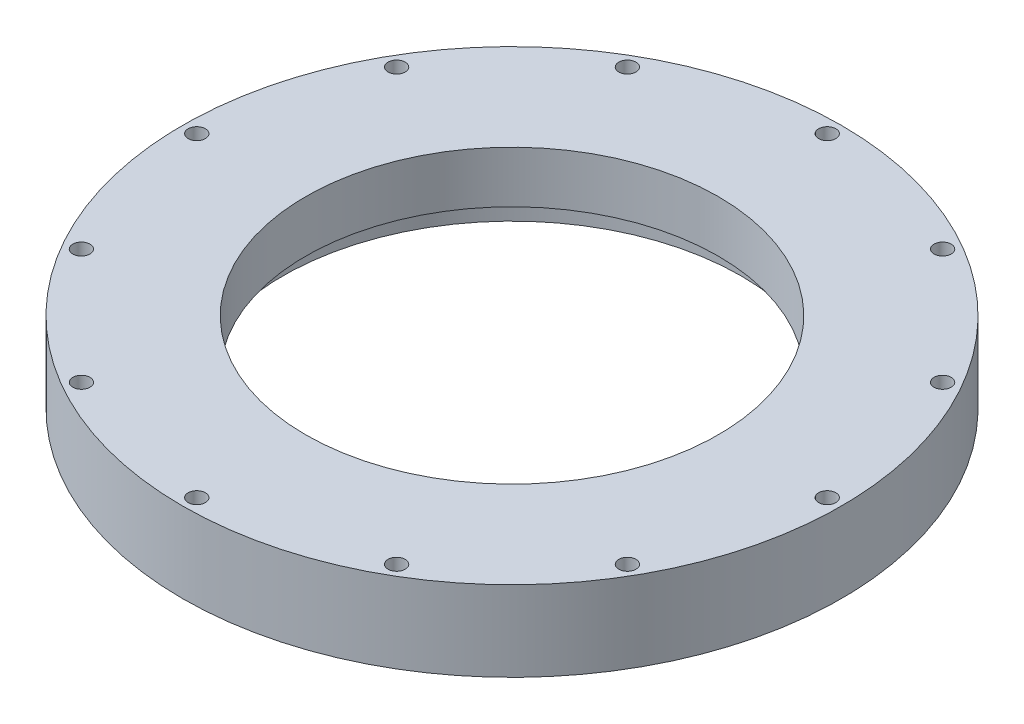
SolidWorks part; units mm, degrees
ref_plane "Front Plane" through (0, 0, 0) normal (0, 0, 1) x (1, 0, 0)
ref_plane "Top Plane" through (0, 0, 0) normal (0, 1, 0) x (1, 0, 0)
ref_plane "Right Plane" through (0, 0, 0) normal (1, 0, 0) x (0, 0, -1)
sketch "Sketch1" plane through (0, 0, 0) normal (0, 1, 0) x (1, 0, 0)
  circle A12 centre (0, 0) radius 40
  circle A13 centre (0, 0) radius 57.5
  circle A14 centre (0, 0) radius 55 construction
  circle A15 centre (0, 55) radius 1.5
  circle A16 centre (27.5, 47.6314) radius 1.5
  circle A17 centre (47.6314, 27.5) radius 1.5
  circle A18 centre (55, 0) radius 1.5
  circle A19 centre (47.6314, -27.5) radius 1.5
  circle A20 centre (27.5, -47.6314) radius 1.5
  circle A21 centre (0, -55) radius 1.5
  circle A22 centre (-27.5, -47.6314) radius 1.5
  circle A23 centre (-47.6314, -27.5) radius 1.5
  circle A24 centre (-55, 0) radius 1.5
  circle A25 centre (-47.6314, 27.5) radius 1.5
  circle A26 centre (-27.5, 47.6314) radius 1.5
  point P1 (0, 0)
  point P28 (0, 0)
  point P56 (0, 0)
  dimension "D4" = 115
  dimension "D5" = 80
  dimension "D6" = 110
  dimension "D7" = 3
  dimension "D8" = 12
extrude "Boss-Extrude1" add sketch "Sketch1" along normal blind 14
sketch "Sketch2" plane through (0, 14, 0) normal (0, 1, 0) x (1, 0, 0)
  circle A0 centre (0, 0) radius 36
  circle A1 centre (0, 0) radius 42.5
  dimension "D1" = 72
  dimension "D2" = 85
extrude "Boss-Extrude2" add sketch "Sketch2" against normal blind 9
sketch "Sketch3" plane through (0, 0, 0) normal (0, -1, 0) x (1, 0, 0)
  circle A0 centre (0, 0) radius 45 construction
  circle A1 centre (0, 45) radius 1.5
  circle A2 centre (24.3288, 37.8564) radius 1.5
  circle A3 centre (40.9334, 18.6937) radius 1.5
  circle A4 centre (44.542, -6.4042) radius 1.5
  circle A5 centre (34.0087, -29.4687) radius 1.5
  circle A6 centre (12.678, -43.1772) radius 1.5
  circle A7 centre (-12.678, -43.1772) radius 1.5
  circle A8 centre (-34.0087, -29.4687) radius 1.5
  circle A9 centre (-44.542, -6.4042) radius 1.5
  circle A10 centre (-40.9334, 18.6937) radius 1.5
  circle A11 centre (-24.3288, 37.8564) radius 1.5
  point P28 (0, 0)
  dimension "D1" = 90
  dimension "D2" = 3
  dimension "D3" = 11
extrude "Cut-Extrude1" cut sketch "Sketch3" against normal blind 5
